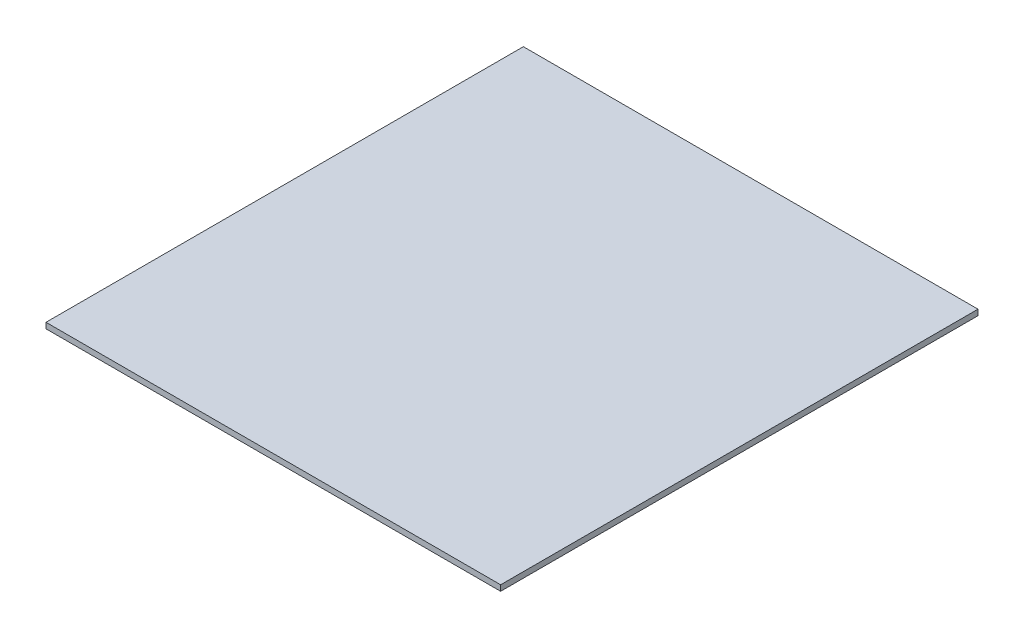
SolidWorks part; units mm, degrees
ref_plane "Front Plane" through (0, 0, 0) normal (0, 0, 1) x (1, 0, 0)
ref_plane "Top Plane" through (0, 0, 0) normal (0, 1, 0) x (1, 0, 0)
ref_plane "Right Plane" through (0, 0, 0) normal (1, 0, 0) x (0, 0, -1)
sketch "Sketch1" plane through (0, 0, 0) normal (0, 1, 0) x (1, 0, 0)
  line L1 (-254, -266.7) -> (254, -266.7)
  line L2 (-254, -266.7) -> (-254, 266.7)
  line L3 (-254, 266.7) -> (254, 266.7)
  line L4 (254, -266.7) -> (254, 266.7)
  line L5 (-254, -266.7) -> (254, 266.7) construction
  line L6 (-254, 266.7) -> (254, -266.7) construction
  point P0 (0, 0)
  dimension "D1" = 508
  dimension "D2" = 533.4
extrude "Boss-Extrude1" add sketch "Sketch1" along normal blind 6.35
